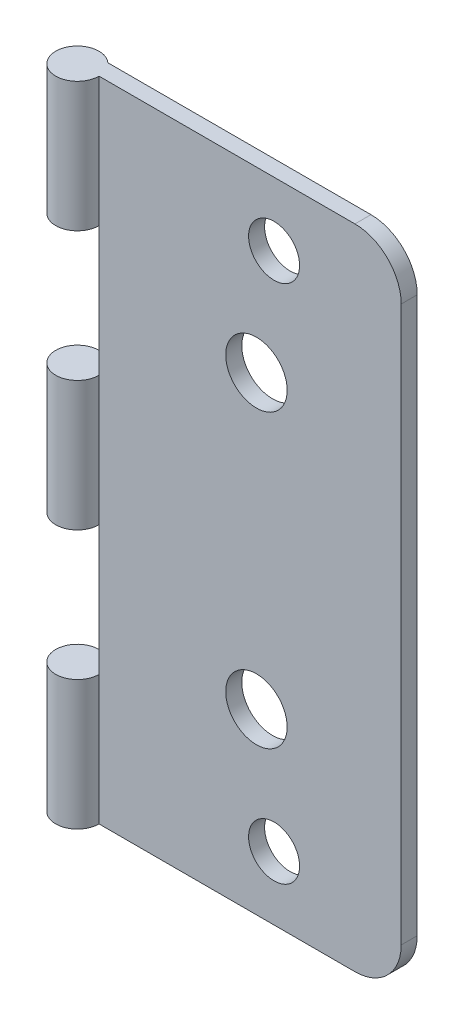
SolidWorks part; units mm, degrees
ref_plane "Front Plane" through (0, 0, 0) normal (0, 0, 1) x (1, 0, 0)
ref_plane "Top Plane" through (0, 0, 0) normal (0, 1, 0) x (1, 0, 0)
ref_plane "Right Plane" through (0, 0, 0) normal (1, 0, 0) x (0, 0, -1)
sketch "Sketch1" plane through (0, 0, 0) normal (0, 1, 0) x (1, 0, 0)
  line L1 (0, 0) -> (44.45, 0)
  line L2 (0, 0) -> (0, 2.2)
  line L3 (0, 2.2) -> (44.45, 2.2)
  line L4 (44.45, 0) -> (44.45, 2.2)
  circle A1 centre (0, 0) radius 2.97
  dimension "D1" = 5.94
  dimension "D2" = 2.2
  dimension "D3" = 44.45
extrude "Boss-Extrude1" add sketch "Sketch1" along normal mid plane 88.9 contours A1 | L1 L4 L3 L2
sketch "Sketch2" plane through (0, 0, 0) normal (0, 0, 1) x (1, 0, 0)
  line L0 (2.97, 44.45) -> (2.97, -44.45) construction
  line L1 (2.97, 26.67) -> (-2.97, 26.67)
  line L2 (2.97, 26.67) -> (2.97, 8.89)
  line L3 (2.97, 8.89) -> (-2.97, 8.89)
  line L4 (-2.97, 26.67) -> (-2.97, 8.89)
  line L5 (-2.97, 44.45) -> (-2.97, -44.45) construction
  line L6 (-2.97, 44.45) -> (-2.97, 26.67) construction
  line L7 (2.97, -8.89) -> (-2.97, -8.89)
  line L8 (2.97, -8.89) -> (2.97, -26.67)
  line L9 (2.97, -26.67) -> (-2.97, -26.67)
  line L10 (-2.97, -8.89) -> (-2.97, -26.67)
  line L11 (-2.97, 8.89) -> (-2.97, -8.89) construction
  line L12 (-2.97, -26.67) -> (-2.97, -44.45) construction
extrude "Cut-Extrude1" cut sketch "Sketch2" against normal through all and the other way through all
fillet "Fillet1" radius 6.35 2 edges at (44.45, -44.45, -1.1) (44.45, 44.45, -1.1)
sketch "Sketch4" plane through (0, 0, 0) normal (0, 0, 1) x (1, 0, 0)
  line L0 (2.97, -44.45) -> (38.1, -44.45) construction
  line L1 (44.45, 38.1) -> (44.45, -38.1) construction
  line L2 (2.97, 44.45) -> (38.1, 44.45) construction
  circle A0 centre (27, 35.7) radius 3.5
  circle A1 centre (27, -35.7) radius 3.5
  dimension "D1" = 7
  dimension "D2" = 8.75
  dimension "D3" = 17.45
  dimension "D4" = 8.75
extrude "Cut-Extrude2" cut sketch "Sketch4" against normal through all
hole_wizard "5/16 Clearance Hole1" positions "Sketch7" profile "Sketch6" hole size "5/16" standard "ANSI Inch" end condition through all
sketch "Sketch7" plane through (0, 0, 0) normal (0, 0, 1) x (1, 0, 0)
  line L0 (24.5813, 20.0103) -> (24.5812, 0) construction
  line L1 (24.5812, 0) -> (24.5812, -20.0103) construction
  circle A0 centre (27, 35.7) radius 3.5 construction
  point P0 (24.5813, 20.0103)
  point P2 (24.5812, -20.0103)
  point P13 (0, 0)
  dimension "D1" = 24.5813
  dimension "D2" = 15.875
sketch "Sketch6" plane through (24.5813, 20.0103, 0) normal (1, 0, 0) x (0, -1, 0)
  line L0 (0, 0) -> (0, 2.97)
  line L1 (0, 2.97) -> (4.2164, 2.97)
  line L2 (4.2164, 2.97) -> (4.2164, 0)
  line L5 (4.2164, 0) -> (0, 0)
  line L11 (0, -6.35) -> (0, 107.95) construction
  dimension "Thru Hole Dia." = 8.4328
  dimension "Thru Hole Depth" = 2.97
